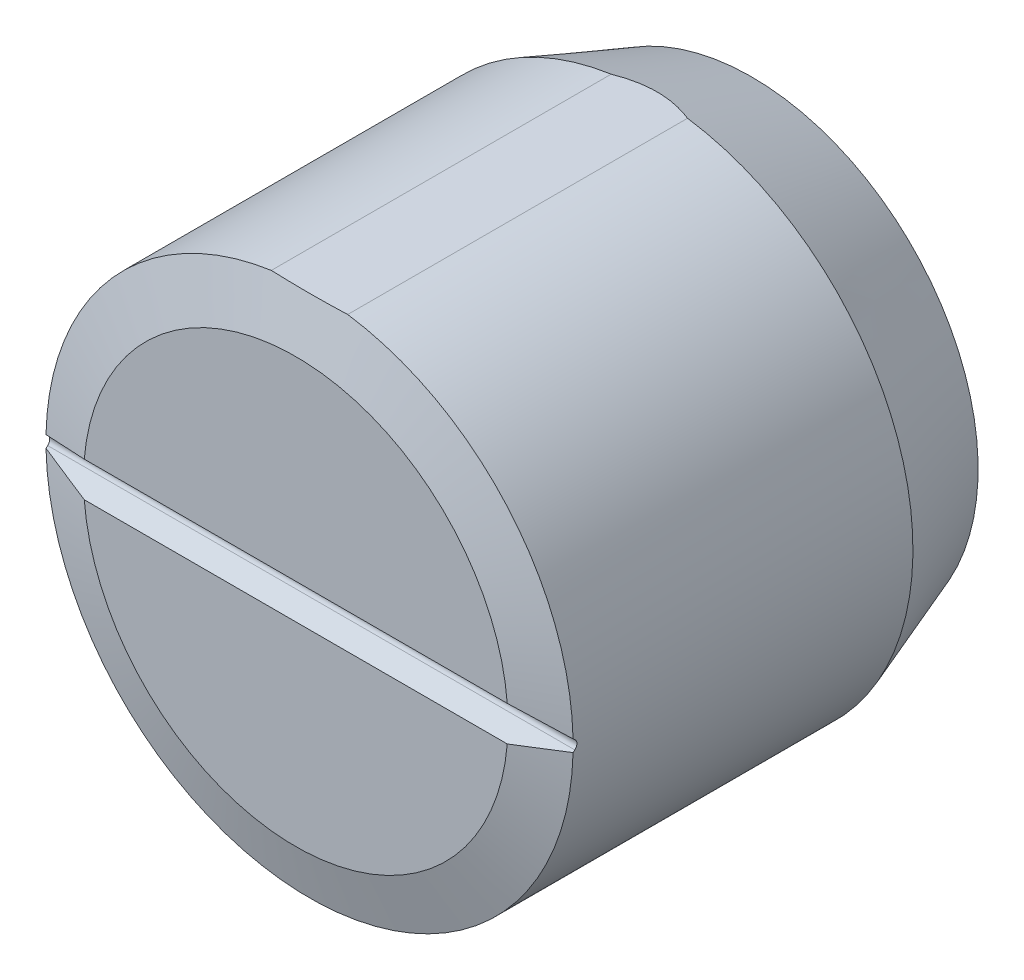
SolidWorks part; units mm, degrees
material "Tungsten Carbide"
ref_plane "Front Plane" through (0, 0, 0) normal (0, 0, 1) x (1, 0, 0)
ref_plane "Top Plane" through (0, 0, 0) normal (0, 1, 0) x (1, 0, 0)
ref_plane "Right Plane" through (0, 0, 0) normal (1, 0, 0) x (0, 0, -1)
sketch "Sketch1" plane through (0, 0, 0) normal (1, 0, 0) x (0, 0, -1)
  line L0 (0, 0) -> (-20.2246, 0) construction
  line L1 (0, 0) -> (0, 7.7311)
  line L2 (0, 7.7311) -> (-3.5, 9.005)
  line L3 (-3.5, 9.005) -> (-15.1097, 9.005)
  line L4 (-15.1097, 9.005) -> (-15.58, 7.25)
  line L5 (-15.58, 7.25) -> (-15.58, 0)
  line L6 (0, 0) -> (-15.58, 0)
  dimension "D1" = 3.5
  dimension "D2" = 18.01
  dimension "D3" = 20
  dimension "D4" = 75
  dimension "D5" = 14.5
  dimension "D6" = 15.58
revolve "Revolve1" add sketch "Sketch1" angle 360 about L0
sketch "Sketch2" plane through (0, 0, 0) normal (1, 0, 0) x (0, -1, 0)
  line L0 (0, 0) -> (0, -16.2913) construction
  line L1 (-0.1527, -15.0509) -> (-0.6, -15.58)
  line L2 (-7.25, -15.58) -> (7.25, -15.58) construction
  line L3 (0.1527, -15.0509) -> (0.6, -15.58)
  line L5 (-0.6, -15.58) -> (0.6, -15.58)
  arc A0 (0.1527, -15.0509) -> (-0.1527, -15.0509) centre (0, -15.18) ccw
  dimension "D1" = 1.2
  dimension "D2" = 0.2
  dimension "D3" = 0.6
extrude "Extrude2" cut sketch "Sketch2" against normal through all and the other way through all
sketch "Sketch3" plane through (0, 0, 15.58) normal (0, 0, 1) x (1, 0, 0)
  line L0 (0, 0) -> (13.672, 0) construction
  line L5 (0, 0) -> (0, 9.8694) construction
  line L7 (-3.7643, 10.91) -> (3.7643, 10.91)
  line L8 (-3.7643, 10.91) -> (-3.7643, 8.91)
  line L9 (-3.7643, 8.91) -> (3.7643, 8.91)
  line L10 (3.7643, 10.91) -> (3.7643, 8.91)
  arc A0 (9.0027, 0.2025) -> (-9.0027, 0.2025) centre (0, 0) ccw construction
  dimension "D1" = 0.095
  dimension "D4" = 8.91
  dimension "D5" = 2
  dimension "D6" = 7.5287
extrude "Extrude3" cut sketch "Sketch3" against normal through all
